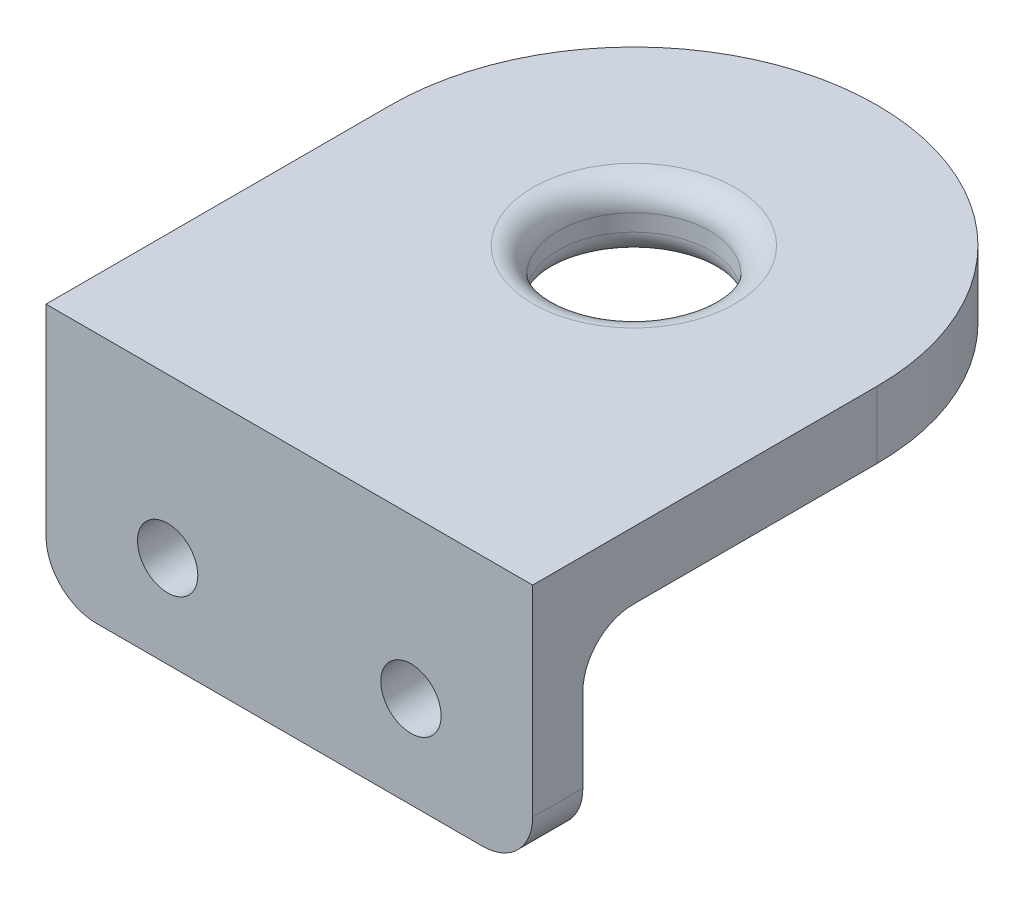
SolidWorks part; units mm, degrees
ref_plane "Front Plane" through (0, 0, 0) normal (0, 0, 1) x (1, 0, 0)
ref_plane "Top Plane" through (0, 0, 0) normal (0, 1, 0) x (1, 0, 0)
ref_plane "Right Plane" through (0, 0, 0) normal (1, 0, 0) x (0, 0, -1)
sketch "Sketch1" plane through (0, 0, 0) normal (0, 1, 0) x (1, 0, 0)
  line L0 (-14.525, 20.57) -> (-14.525, 0)
  line L1 (-14.525, 0) -> (14.525, 0)
  line L2 (14.525, 0) -> (14.525, 20.57)
  circle A0 centre (0, 20.57) radius 4.525
  arc A1 (14.525, 20.57) -> (-14.525, 20.57) centre (0, 20.57) ccw
  circle A2 centre (0, 20.57) radius 14.525 construction
  dimension "D1" = 9.05
  dimension "D2" = 20.57
  dimension "D3" = 10
extrude "Boss-Extrude1" add sketch "Sketch1" along normal blind 4
sketch "Sketch2" plane through (0, 0, 0) normal (0, 0, 1) x (1, 0, 0)
  line L0 (14.525, 4) -> (14.525, 0) construction
  line L1 (-14.525, 4) -> (14.525, 4)
  line L2 (-14.525, 4) -> (-14.525, -11)
  line L3 (-14.525, -11) -> (14.525, -11)
  line L4 (14.525, 4) -> (14.525, -11)
  line L5 (-14.525, 4) -> (14.525, -11) construction
  line L6 (-14.525, -11) -> (14.525, 4) construction
  point P4 (0, -3.5)
  dimension "D1" = 15
extrude "Boss-Extrude2" add sketch "Sketch2" against normal blind 3
sketch "Sketch3" plane through (0, 0, -3) normal (0, 0, -1) x (-1, 0, 0)
  line L0 (-14.525, -5.5) -> (14.525, -5.5) construction
  line L1 (-14.525, -11) -> (-14.525, 0) construction
  line L2 (14.525, 0) -> (14.525, -11) construction
  line L3 (0, 0) -> (0, -11) construction
  line L4 (14.525, -11) -> (-14.525, -11) construction
  circle A0 centre (-7.2625, -5.5) radius 1.8
  circle A1 centre (7.2625, -5.5) radius 1.8
  point P13 (-7.3108, -3)
  dimension "D2" = 3.6
  dimension "D1" = 7.2625
extrude "Cut-Extrude1" cut sketch "Sketch3" against normal through all
fillet "Fillet1" radius 3 3 edges at (-14.525, -11, -1.5) (14.525, -11, -1.5) (0, 0, -3)
fillet "Fillet2" radius 1.5 2 edges at (0, 0, -16.045) (0, 4, -16.045)
